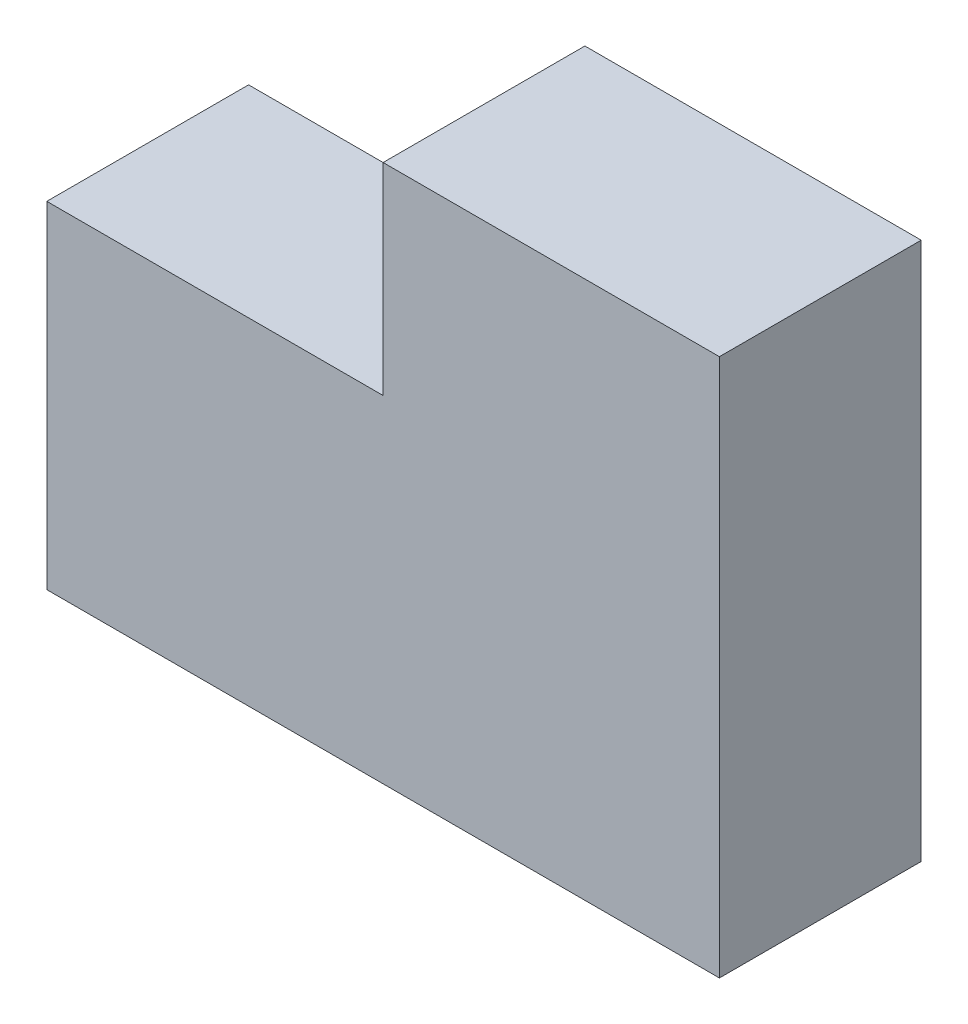
SolidWorks part; units mm, degrees
material "Balsa"
ref_plane "Alzado" through (0, 0, 0) normal (0, 0, 1) x (1, 0, 0)
ref_plane "Planta" through (0, 0, 0) normal (0, 1, 0) x (1, 0, 0)
ref_plane "Vista lateral" through (0, 0, 0) normal (1, 0, 0) x (0, 0, -1)
sketch "Croquis1" plane through (0, 0, 0) normal (0, 0, 1) x (1, 0, 0)
  line L0 (0, 0) -> (10, 0)
  line L1 (10, 0) -> (10, 8)
  line L2 (10, 8) -> (5, 8)
  line L3 (5, 8) -> (5, 5)
  line L4 (5, 5) -> (0, 5)
  line L5 (0, 5) -> (0, 0)
  dimension "D1" = 5
  dimension "D2" = 5
  dimension "D3" = 5
  dimension "D4" = 3
extrude "Saliente-Extruir1" add sketch "Croquis1" along normal blind 3
